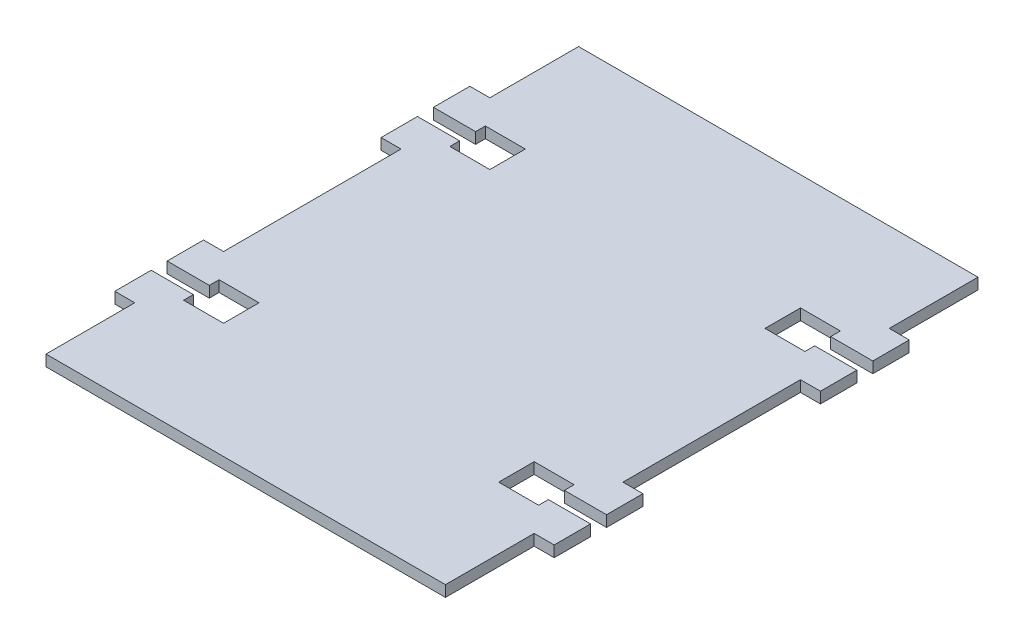
SolidWorks part; units mm, degrees
material "Acrylic (Medium-high impact)"
ref_plane "Front Plane" through (0, 0, 0) normal (0, 0, 1) x (1, 0, 0)
ref_plane "Top Plane" through (0, 0, 0) normal (0, 1, 0) x (1, 0, 0)
ref_plane "Right Plane" through (0, 0, 0) normal (1, 0, 0) x (0, 0, -1)
sketch "Sketch1" plane through (0, 0, 0) normal (0, 1, 0) x (1, 0, 0)
  line L0 (49.5, 40) -> (-49.5, 20) construction
  line L1 (-45, -60) -> (45, -60)
  line L2 (-45, -60) -> (-45, 60)
  line L3 (-45, 60) -> (45, 60)
  line L4 (45, -60) -> (45, 60)
  line L5 (-45, -60) -> (45, 60) construction
  line L6 (-45, 60) -> (45, -60) construction
  line L7 (-49.5, -40) -> (49.5, -40)
  line L8 (-49.5, -40) -> (-49.5, 40)
  line L9 (-49.5, 40) -> (49.5, 40)
  line L10 (49.5, -40) -> (49.5, 40)
  line L11 (-49.5, -40) -> (49.5, 40) construction
  line L12 (-49.5, 40) -> (49.5, -40) construction
  line L13 (-49.5, -20) -> (49.5, -20)
  line L14 (-49.5, -20) -> (-49.5, 20)
  line L15 (-49.5, 20) -> (49.5, 20)
  line L16 (49.5, -20) -> (49.5, 20)
  line L17 (-49.5, -20) -> (49.5, 20) construction
  line L18 (-49.5, 20) -> (49.5, -20) construction
  line L19 (-49.5, -20) -> (49.5, -40) construction
  line L21 (49.5, 28.2) -> (-49.5, 28.2)
  line L22 (49.5, 28.2) -> (49.5, 31.8)
  line L23 (49.5, 31.8) -> (-49.5, 31.8)
  line L24 (-49.5, 28.2) -> (-49.5, 31.8)
  line L25 (49.5, 28.2) -> (-49.5, 31.8) construction
  line L26 (49.5, 31.8) -> (-49.5, 28.2) construction
  line L27 (49.5, -31.8) -> (-49.5, -31.8)
  line L28 (49.5, -31.8) -> (49.5, -28.2)
  line L29 (49.5, -28.2) -> (-49.5, -28.2)
  line L30 (-49.5, -31.8) -> (-49.5, -28.2)
  line L31 (49.5, -31.8) -> (-49.5, -28.2) construction
  line L32 (49.5, -28.2) -> (-49.5, -31.8) construction
  line L33 (35.5, 28.2) -> (-35.5, 28.2)
  line L34 (35.5, 28.2) -> (35.5, 31.8)
  line L35 (35.5, 31.8) -> (-35.5, 31.8)
  line L36 (-35.5, 28.2) -> (-35.5, 31.8)
  line L37 (35.5, 28.2) -> (-35.5, 31.8) construction
  line L38 (35.5, 31.8) -> (-35.5, 28.2) construction
  line L39 (35.5, -31.8) -> (-35.5, -31.8)
  line L40 (35.5, -31.8) -> (35.5, -28.2)
  line L41 (35.5, -28.2) -> (-35.5, -28.2)
  line L42 (-35.5, -31.8) -> (-35.5, -28.2)
  line L43 (35.5, -31.8) -> (-35.5, -28.2) construction
  line L44 (35.5, -28.2) -> (-35.5, -31.8) construction
  line L45 (-31, 26) -> (-40, 26)
  line L46 (-31, 26) -> (-31, 34)
  line L47 (-31, 34) -> (-40, 34)
  line L48 (-40, 26) -> (-40, 34)
  line L49 (-31, 26) -> (-40, 34) construction
  line L50 (-31, 34) -> (-40, 26) construction
  line L51 (31, 26) -> (40, 26)
  line L52 (31, 26) -> (31, 34)
  line L53 (31, 34) -> (40, 34)
  line L54 (40, 26) -> (40, 34)
  line L55 (31, 26) -> (40, 34) construction
  line L56 (31, 34) -> (40, 26) construction
  line L57 (-31, -34) -> (-40, -34)
  line L58 (-31, -34) -> (-31, -26)
  line L59 (-31, -26) -> (-40, -26)
  line L60 (-40, -34) -> (-40, -26)
  line L61 (-31, -34) -> (-40, -26) construction
  line L62 (-31, -26) -> (-40, -34) construction
  line L63 (31, -34) -> (40, -34)
  line L64 (31, -34) -> (31, -26)
  line L65 (31, -26) -> (40, -26)
  line L66 (40, -34) -> (40, -26)
  line L67 (31, -34) -> (40, -26) construction
  line L68 (31, -26) -> (40, -34) construction
  point P0 (0, 0)
  point P6 (0, 0)
  point P11 (0, 0)
  point P16 (0, 30)
  point P21 (0, -30)
  point P26 (0, 30)
  point P31 (0, -30)
  point P36 (-35.5, 30)
  point P41 (35.5, 30)
  point P46 (-35.5, -30)
  point P51 (35.5, -30)
  dimension "D1" = 20
  dimension "D2" = 20
  dimension "D3" = 90
  dimension "D4" = 99
  dimension "D5" = 40
  dimension "D6" = 3.6
  dimension "D7" = 3.6
  dimension "D8" = 14
  dimension "D9" = 14
  dimension "D10" = 9
  dimension "D11" = 8
  dimension "D12" = 8
  dimension "D13" = 9
  dimension "D14" = 8
  dimension "D15" = 9
  dimension "D16" = 8
  dimension "D17" = 9
extrude "Boss-Extrude1" add sketch "Sketch1" along normal blind 2.5 contours L2 L9 L4 L3 | L54 L23 L4 L9 L2 L48 L47 L46 L35 L52 L53 | L23 L2 L9 L8 | L2 L21 L8 L15 | L54 L51 L52 L33 L46 L45 L48 L21 L2 L15 L4 | L33 L52 L35 L46 | L15 L2 L13 L4 | L66 L29 L4 L13 L2 L60 L59 L58 L41 L64 L65 | L29 L2 L13 L8 | L2 L27 L8 L7 | L66 L63 L64 L39 L58 L57 L60 L27 L2 L7 L4 | L39 L64 L41 L58 | L29 L10 L13 L4 | L10 L27 L4 L7 | L10 L21 L4 L15 | L23 L10 L9 L4 | L7 L2 L1 L4
